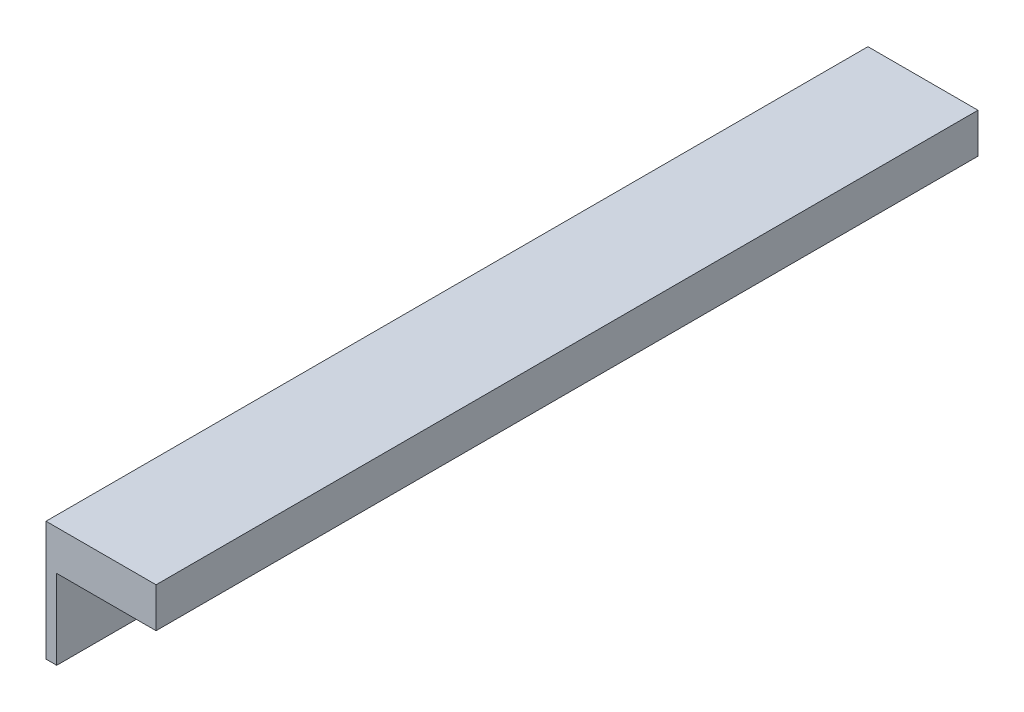
SolidWorks part; units mm, degrees
ref_plane "Front Plane" through (0, 0, 0) normal (0, 0, 1) x (1, 0, 0)
ref_plane "Top Plane" through (0, 0, 0) normal (0, 1, 0) x (1, 0, 0)
ref_plane "Right Plane" through (0, 0, 0) normal (1, 0, 0) x (0, 0, -1)
sketch "Sketch1" plane through (0, 0, 0) normal (0, 1, 0) x (1, 0, 0)
  line L1 (-54.762, 30.9684) -> (54, 30.9684)
  line L2 (-54.762, 30.9684) -> (-54.762, -30.9684)
  line L3 (-54.762, -30.9684) -> (54, -30.9684)
  line L4 (54, 30.9684) -> (54, -30.9684)
  point P0 (0, 0)
extrude "Boss-Extrude1" add sketch "Sketch1" along normal blind 2
sketch "Sketch2" plane through (0, 2, 0) normal (0, 1, 0) x (1, 0, 0)
  line L0 (-54.762, 30.9684) -> (-50.8149, 26.4778)
  line L1 (-54.762, 30.9684) -> (-54.762, -30.9684) construction
  line L3 (-54.762, 0) -> (54, 0) construction
  line L4 (54, -30.9684) -> (54, 30.9684) construction
  line L5 (-0.381, 30.9684) -> (-0.381, -30.9684) construction
  line L6 (54, 30.9684) -> (-54.762, 30.9684) construction
  line L7 (-54.762, -30.9684) -> (54, -30.9684) construction
  circle A0 centre (-50.8149, 26.4778) radius 2.4
  point P2 (-50.8149, 26.4778)
ref_plane "Plane1" through (0, 0, 0) normal (0, 0, 1) x (1, 0, 0)
ref_plane "Plane2" through (-0.381, 0, 0) normal (-1, 0, 0) x (0, 0, 1)
extrude "Cut-Extrude1" cut sketch "Sketch2" against normal through all and the other way through all contours A0
mirror "Mirror1" about plane through (0, 0, 0) normal (0, 0, 1) of "Cut-Extrude1"
mirror "Mirror2" about plane through (-0.381, 0, 0) normal (-1, 0, 0) of "Mirror1", "Cut-Extrude1"
sketch "Sketch3" plane through (0, 2, 0) normal (0, 1, 0) x (1, 0, 0)
  line L1 (-47.0124, -28.2777) -> (47.0124, -28.2777)
  line L2 (-47.0124, -28.2777) -> (-47.0124, 28.2777)
  line L3 (-47.0124, 28.2777) -> (47.0124, 28.2777)
  line L4 (47.0124, -28.2777) -> (47.0124, 28.2777)
  line L5 (-47.0124, -28.2777) -> (47.0124, 28.2777) construction
  line L6 (-47.0124, 28.2777) -> (47.0124, -28.2777) construction
  point P0 (0, 0)
extrude "Cut-Extrude2" cut sketch "Sketch3" against normal through all
sketch "Sketch4" plane through (0, 2, 0) normal (0, 1, 0) x (1, 0, 0)
  line L0 (-34.0652, 0) -> (34.0652, 0) construction
  line L1 (-47.7447, -25.6583) -> (-52.7454, -25.6583)
  line L2 (-47.7447, -25.6583) -> (-47.7447, 25.6583)
  line L3 (-47.7447, 25.6583) -> (-52.7454, 25.6583)
  line L4 (-52.7454, -25.6583) -> (-52.7454, 25.6583)
  line L5 (-47.7447, -25.6583) -> (-52.7454, 25.6583) construction
  line L6 (-47.7447, 25.6583) -> (-52.7454, -25.6583) construction
  point P0 (-50.2451, 0)
extrude "Cut-Extrude3" [suppressed] cut sketch "Sketch4" against normal through all
sketch "Sketch5" plane through (0, 2, 0) normal (0, 1, 0) x (1, 0, 0)
  line L0 (-47.0648, 30.9684) -> (-47.0648, -30.9684)
  line L1 (54, 30.9684) -> (-54.762, 30.9684) construction
  line L2 (-54.762, -30.9684) -> (54, -30.9684) construction
  line L3 (-47.0648, -30.9684) -> (54, -30.9684)
  line L4 (54, -30.9684) -> (54, 30.9684)
  line L5 (54, 30.9684) -> (-47.0648, 30.9684)
extrude "Cut-Extrude4" [suppressed] cut sketch "Sketch5" against normal blind 10
sketch "Sketch6" plane through (0, 2, 0) normal (0, 1, 0) x (1, 0, 0)
  line L2 (-47.2763, 30.9684) -> (-47.2763, -30.9684)
  line L3 (-54.762, -30.9684) -> (54, -30.9684) construction
  line L4 (-47.2763, -30.9684) -> (54, -30.9684)
  line L5 (54, -30.9684) -> (54, 30.9684)
  line L6 (54, 30.9684) -> (-47.2763, 30.9684)
  point P0 (0, 0)
extrude "Cut-Extrude5" cut sketch "Sketch6" against normal blind 10
sketch "Sketch8" plane through (0, 2, 0) normal (0, 1, 0) x (1, 0, 0)
  line L0 (-54.762, 30.9684) -> (-55.5705, 30.9684)
  line L1 (-55.5705, 30.9684) -> (-55.5705, -30.9684)
  line L2 (-55.5705, -30.9684) -> (-54.762, -30.9684)
  line L3 (-54.762, -30.9684) -> (-54.762, 30.9684)
extrude "Boss-Extrude2" add sketch "Sketch8" against normal blind 8
sketch "Sketch9" plane through (0, 2, 0) normal (0, 1, 0) x (1, 0, 0)
  line L0 (-55.5705, 30.9684) -> (-47.2763, 30.9684)
  line L1 (-47.2763, 30.9684) -> (-47.2763, -30.9684)
  line L2 (-47.2763, -30.9684) -> (-55.5705, -30.9684)
  line L3 (-55.5705, -30.9684) -> (-55.5705, 30.9684)
sketch "Sketch10" plane through (0, 2, 0) normal (0, 1, 0) x (1, 0, 0)
  line L0 (-55.5705, 30.9684) -> (-47.2763, 30.9684)
  line L1 (-47.2763, 30.9684) -> (-47.2763, -30.9684)
  line L2 (-47.2763, -30.9684) -> (-55.5705, -30.9684)
  line L3 (-55.5705, -30.9684) -> (-55.5705, 30.9684)
extrude "Boss-Extrude4" add sketch "Sketch10" along normal blind 1
sketch "Sketch11" plane through (0, 2, 0) normal (0, -1, 0) x (1, 0, 0)
  circle A0 centre (-50.8149, -26.4778) radius 2.4
  circle A1 centre (-50.8149, 26.4778) radius 2.4
extrude "Cut-Extrude6" cut sketch "Sketch11" against normal blind 0.5
